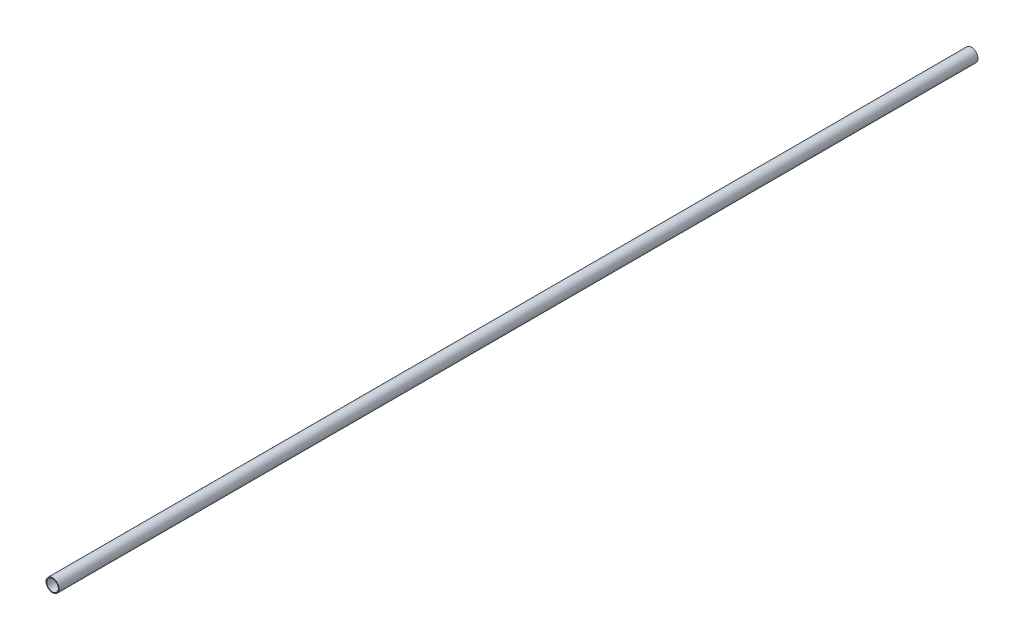
SolidWorks part; units mm, degrees
material "Thornel Mat VMA"
ref_plane "Front Plane" through (0, 0, 0) normal (0, 0, 1) x (1, 0, 0)
ref_plane "Top Plane" through (0, 0, 0) normal (0, 1, 0) x (1, 0, 0)
ref_plane "Right Plane" through (0, 0, 0) normal (1, 0, 0) x (0, 0, -1)
sketch "Sketch1" plane through (0, 0, 0) normal (0, 0, 1) x (1, 0, 0)
  circle A0 centre (0, 0) radius 6.5
  circle A1 centre (0, 0) radius 5.75
  dimension "D1" = 13
  dimension "D2" = 11.5
extrude "Boss-Extrude1" add sketch "Sketch1" along normal mid plane 914.4
